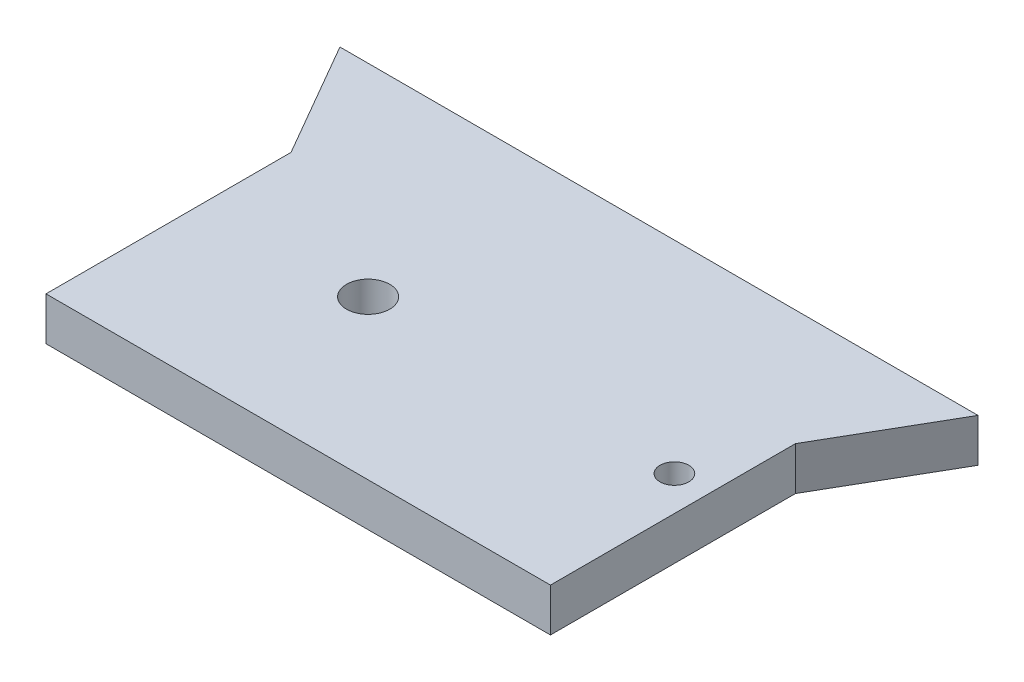
SolidWorks part; units mm, degrees
ref_plane "前视基准面" through (0, 0, 0) normal (0, 0, 1) x (1, 0, 0)
ref_plane "上视基准面" through (0, 0, 0) normal (0, 1, 0) x (1, 0, 0)
ref_plane "右视基准面" through (0, 0, 0) normal (1, 0, 0) x (0, 0, -1)
sketch "草图1" plane through (0, 0, 0) normal (0, 1, 0) x (1, 0, 0)
  line L12 (-28.8383, 9.2114) -> (-28.8383, -7.7886)
  line L13 (-28.8383, -7.7886) -> (6.1617, -7.7886)
  line L14 (6.1617, -7.7886) -> (6.1617, 9.2114)
  line L15 (6.1617, 9.2114) -> (10.7971, 17.24)
  line L16 (10.7971, 17.24) -> (-33.4736, 17.24)
  line L17 (-33.4736, 17.24) -> (-28.8383, 9.2114)
  circle A3 centre (3.7617, 3.2114) radius 1
  circle A4 centre (-17.4883, 3.2114) radius 1.5
extrude "凸台-拉伸1" add sketch "草图1" along normal blind 3
